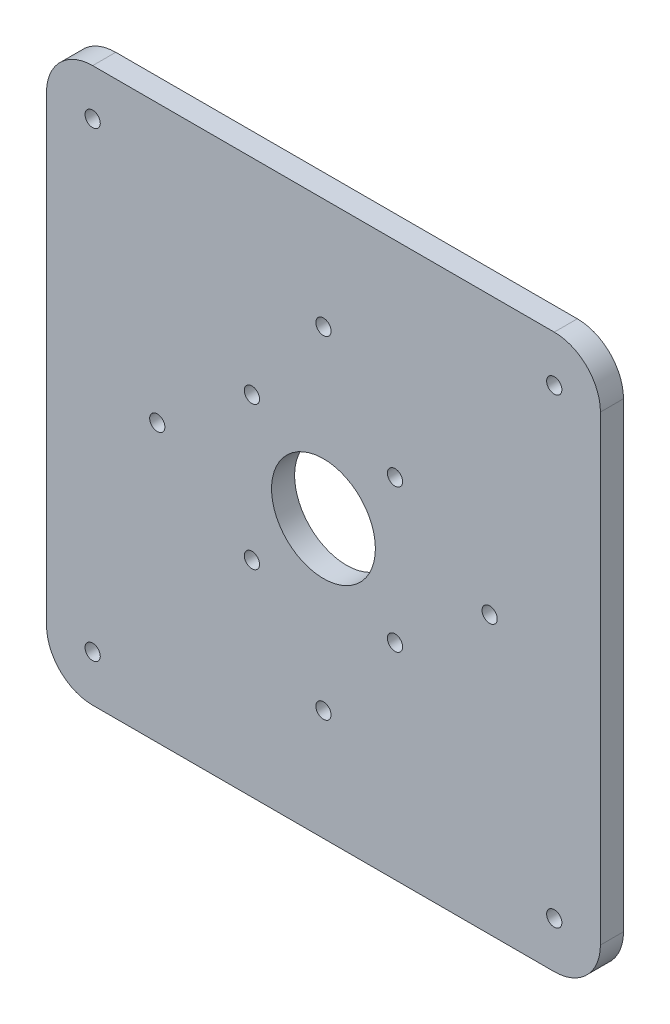
SolidWorks part; units mm, degrees
ref_plane "Спереди" through (0, 0, 0) normal (0, 0, 1) x (1, 0, 0)
ref_plane "Сверху" through (0, 0, 0) normal (0, 1, 0) x (1, 0, 0)
ref_plane "Справа" through (0, 0, 0) normal (1, 0, 0) x (0, 0, -1)
other "Configuration Table"
sketch "Eskiz_kontur" plane through (0, 0, 0) normal (0, 0, 1) x (1, 0, 0)
  line L0 (-60, -50) -> (-60, 50)
  line L1 (50, -60) -> (-50, -60)
  line L2 (-50, 60) -> (50, 60)
  line L3 (60, 50) -> (60, -50)
  arc A0 (-50, -60) -> (-60, -50) centre (-50, -50) cw
  arc A1 (-60, 50) -> (-50, 60) centre (-50, 50) cw
  arc A2 (60, -50) -> (50, -60) centre (50, -50) cw
  arc A3 (50, 60) -> (60, 50) centre (50, 50) cw
extrude "Plastina" add sketch "Eskiz_kontur" along normal blind 5
sketch "Eskiz_otverstiya" plane through (0, 0, 0) normal (0, 0, 1) x (1, 0, 0)
  circle A0 centre (-50, -50) radius 1.65
  circle A1 centre (0, -36) radius 1.65
  circle A2 centre (-15.5, -15.5) radius 1.65
  circle A3 centre (0, 0) radius 11.25
  circle A4 centre (50, -50) radius 1.65
  circle A5 centre (15.5, -15.5) radius 1.65
  circle A6 centre (36, 0) radius 1.65
  circle A7 centre (-36, 0) radius 1.65
  circle A8 centre (-15.5, 15.5) radius 1.65
  circle A9 centre (-50, 50) radius 1.65
  circle A10 centre (0, 36) radius 1.65
  circle A11 centre (15.5, 15.5) radius 1.65
  circle A12 centre (50, 50) radius 1.65
  dimension "d1" = 3.3
  dimension "d2" = 3.3
  dimension "d3" = 3.3
  dimension "d4" = 22.5
  dimension "d5" = 3.3
  dimension "d6" = 3.3
  dimension "d7" = 3.3
  dimension "d8" = 3.3
  dimension "d9" = 3.3
  dimension "d10" = 3.3
  dimension "d11" = 3.3
  dimension "d12" = 3.3
  dimension "d13" = 3.3
extrude "Otverstiya" cut sketch "Eskiz_otverstiya" against normal through all and the other way through all
equation "\"T3\" = 3"
equation "\"T5\" = 5"
equation "\"D_M3\" = 3.3"
equation "\"D_M2\" = 2.2"
equation "\"D_M3_TAP\" = 2.5"
equation "\"D_M4\" = 4.5"
equation "\"L1\" = 100"
equation "\"L2\" = 100"
equation "\"D1@Plastina\" = \"T5\""
equation "\"d1@Eskiz_otverstiya\" = \"D_M3\""
equation "\"d2@Eskiz_otverstiya\" = \"D_M3\""
equation "\"d3@Eskiz_otverstiya\" = \"D_M3\""
equation "\"d5@Eskiz_otverstiya\" = \"D_M3\""
equation "\"d6@Eskiz_otverstiya\" = \"D_M3\""
equation "\"d7@Eskiz_otverstiya\" = \"D_M3\""
equation "\"d8@Eskiz_otverstiya\" = \"D_M3\""
equation "\"d9@Eskiz_otverstiya\" = \"D_M3\""
equation "\"d10@Eskiz_otverstiya\" = \"D_M3\""
equation "\"d11@Eskiz_otverstiya\" = \"D_M3\""
equation "\"d12@Eskiz_otverstiya\" = \"D_M3\""
equation "\"d13@Eskiz_otverstiya\" = \"D_M3\""
